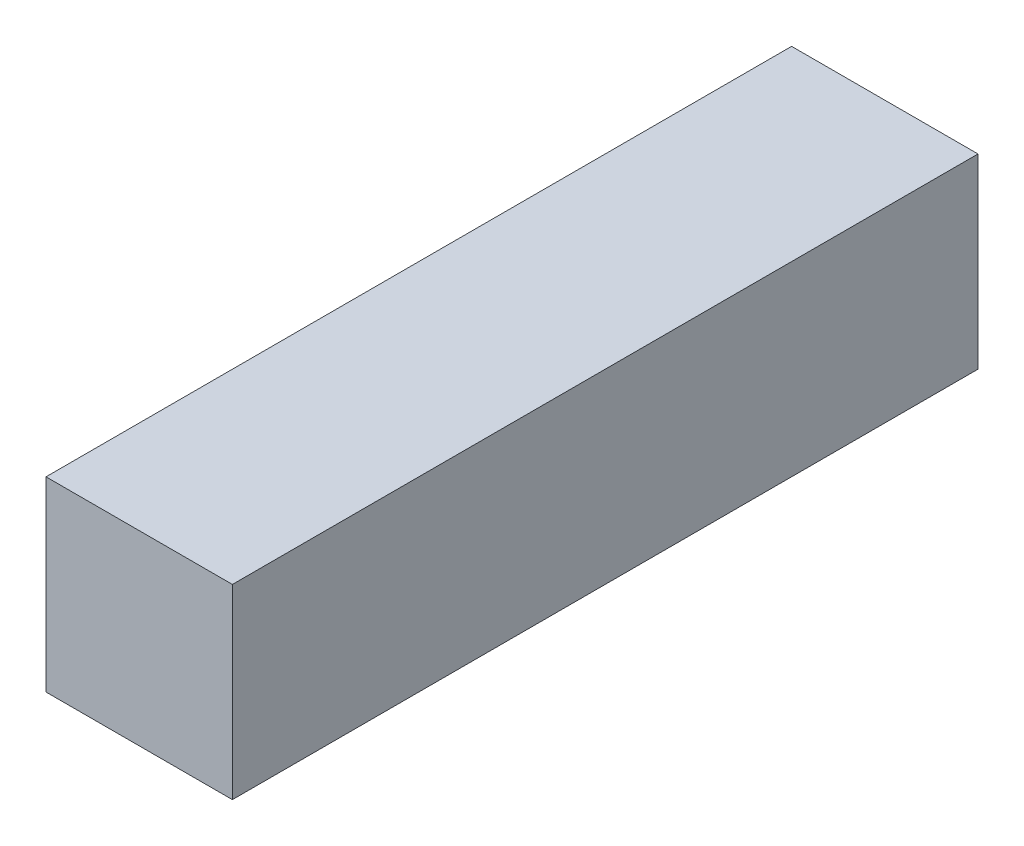
SolidWorks part; units mm, degrees
material "Plain Carbon Steel"
ref_plane "Front Plane" through (0, 0, 0) normal (0, 0, 1) x (1, 0, 0)
ref_plane "Top Plane" through (0, 0, 0) normal (0, 1, 0) x (1, 0, 0)
ref_plane "Right Plane" through (0, 0, 0) normal (1, 0, 0) x (0, 0, -1)
sketch "Sketch1" plane through (0, 0, 0) normal (0, 0, 1) x (1, 0, 0)
  line L1 (1.5875, -1.5875) -> (-1.5875, -1.5875)
  line L2 (1.5875, -1.5875) -> (1.5875, 1.5875)
  line L3 (1.5875, 1.5875) -> (-1.5875, 1.5875)
  line L4 (-1.5875, -1.5875) -> (-1.5875, 1.5875)
  line L5 (1.5875, -1.5875) -> (-1.5875, 1.5875) construction
  line L6 (1.5875, 1.5875) -> (-1.5875, -1.5875) construction
  point P0 (0, 0)
  dimension "D1" = 3.175
  dimension "D2" = 3.175
extrude "Boss-Extrude1" add sketch "Sketch1" along normal blind 12.7
